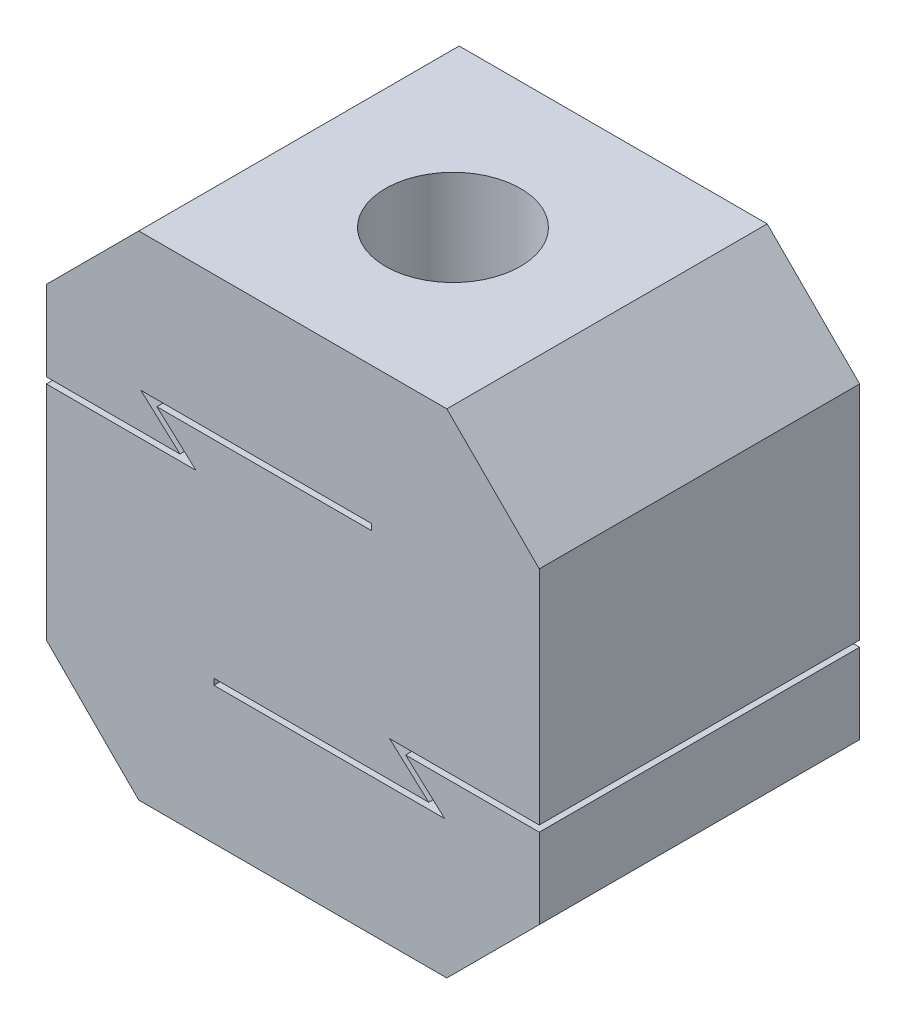
SolidWorks part; units mm, degrees
ref_plane "Front Plane" through (0, 0, 0) normal (0, 0, 1) x (1, 0, 0)
ref_plane "Top Plane" through (0, 0, 0) normal (0, 1, 0) x (1, 0, 0)
ref_plane "Right Plane" through (0, 0, 0) normal (1, 0, 0) x (0, 0, -1)
sketch "Sketch1" plane through (0, 0, 0) normal (0, 0, 1) x (1, 0, 0)
  line L1 (-40, 40) -> (40, 40)
  line L2 (-40, 40) -> (-40, -40)
  line L3 (-40, -40) -> (40, -40)
  line L4 (40, 40) -> (40, -40)
  line L5 (-40, 40) -> (40, -40) construction
  line L6 (-40, -40) -> (40, 40) construction
  point P0 (0, 0)
  dimension "D1" = 80
  dimension "D2" = 80
extrude "Boss-Extrude1" add sketch "Sketch1" along normal blind 52
chamfer "Chamfer1" distance 15 angle 45 4 edges at (-40, -40, 26) (40, -40, 26) (40, 40, 26) (-40, 40, 26)
sketch "Sketch2" plane through (0, 0, 0) normal (0, 0, -1) x (-1, 0, 0)
  line L0 (-47.5544, 11) -> (54.3479, 11) construction
  line L1 (25, -40) -> (-25, -40) construction
  line L5 (-40, 0) -> (40, 0) construction
  line L6 (-40, -25) -> (-40, 25) construction
  line L7 (40, 25) -> (40, -25) construction
  line L8 (0, 0) -> (0, -17.6169) construction
  line L9 (44.088, 11) -> (15.7221, 11)
  line L10 (22.062, 16.7696) -> (15.7221, 11)
  line L11 (22.062, 16.7696) -> (-12.8106, 16.7696)
  line L12 (-22.062, -16.7696) -> (12.8106, -16.7696)
  line L13 (-43.1519, -11) -> (-15.7221, -11)
  line L14 (-22.062, -16.7696) -> (-15.7221, -11)
  dimension "D1" = 51
extrude "Cut-Extrude-Thin2" cut sketch "Sketch2" against normal through all both and the other way through all thin
sketch "Sketch3" plane through (0, 40, 0) normal (0, 1, 0) x (1, 0, 0)
  line L0 (0, 0) -> (0, -52) construction
  line L1 (25, 0) -> (-25, 0) construction
  line L2 (25, -52) -> (-25, -52) construction
  circle A0 centre (0, -26) radius 10.96
  dimension "D1" = 21.92
extrude "Cut-Extrude2" cut sketch "Sketch3" against normal blind 16
mirror "Mirror1" about plane through (0, 0, 0) normal (0, 1, 0) of "Cut-Extrude2"
